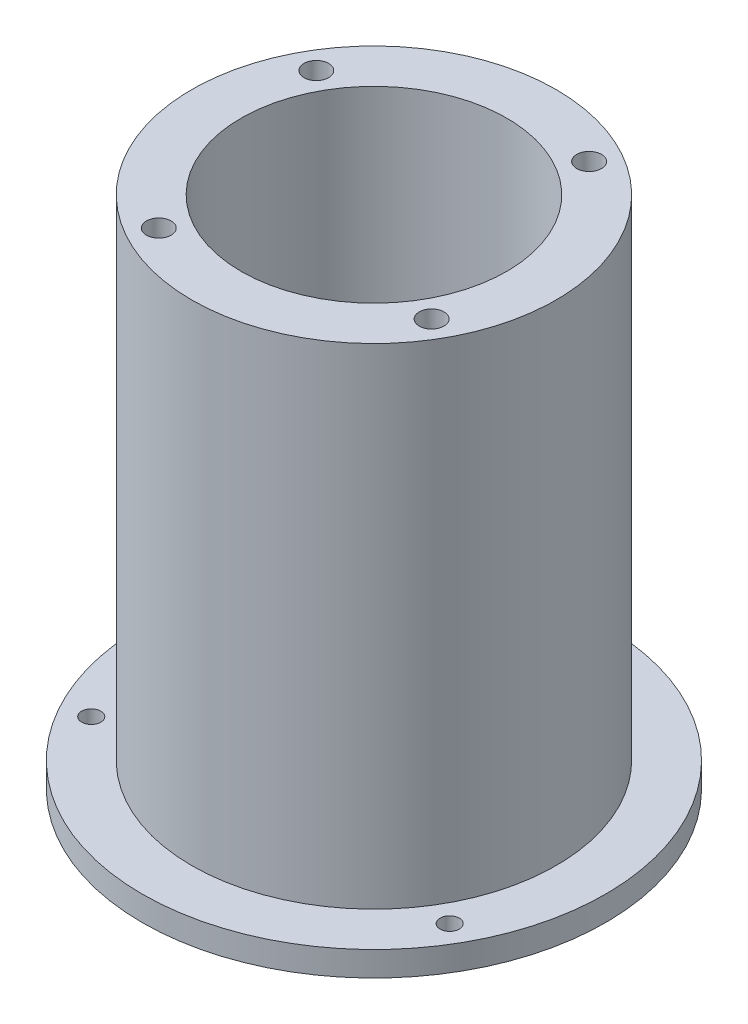
SolidWorks part; units mm, degrees
ref_plane "Front Plane" through (0, 0, 0) normal (0, 0, 1) x (1, 0, 0)
ref_plane "Top Plane" through (0, 0, 0) normal (0, 1, 0) x (1, 0, 0)
ref_plane "Right Plane" through (0, 0, 0) normal (1, 0, 0) x (0, 0, -1)
sketch "Sketch1" plane through (0, 0, 0) normal (0, 1, 0) x (1, 0, 0)
  circle A0 centre (0, 0) radius 37.5
  circle A1 centre (0, 0) radius 21.5
  dimension "D1" = 43
  dimension "D2" = 75
extrude "Boss-Extrude1" add sketch "Sketch1" along normal blind 4
sketch "Sketch2" plane through (0, 4, 0) normal (0, 1, 0) x (1, 0, 0)
  circle A0 centre (0, 0) radius 29.5
  circle A1 centre (0, 0) radius 21.5
  dimension "D1" = 59
  dimension "D2" = 43
extrude "Boss-Extrude2" add sketch "Sketch2" along normal blind 79.3
sketch "Sketch3" plane through (0, 4, 0) normal (0, 1, 0) x (1, 0, 0)
  circle A0 centre (0, 33.5) radius 1.55
  dimension "D1" = 33.5
  dimension "D2" = 3.1
extrude "Cut-Extrude1" cut sketch "Sketch3" against normal through all
pattern_circular "CirPattern1" count 3 over 360 about axis through (0, 0, 0) along (0, 1, 0) of "Cut-Extrude1"
sketch "Sketch4" plane through (0, 83.3, 0) normal (0, 1, 0) x (1, 0, 0)
  line L0 (0, 0) -> (0, 29.5)
  circle A0 centre (0, 0) radius 29.5 construction
  circle A1 centre (-22.0836, 12.75) radius 2
  dimension "D1" = 4
  dimension "D2" = 25.5
  dimension "D3" = 60
extrude "Cut-Extrude2" cut sketch "Sketch4" against normal blind 6 contours A1
pattern_circular "CirPattern2" count 4 over 360 about axis through (0, 0, 0) along (0, 1, 0) of "Cut-Extrude2"
